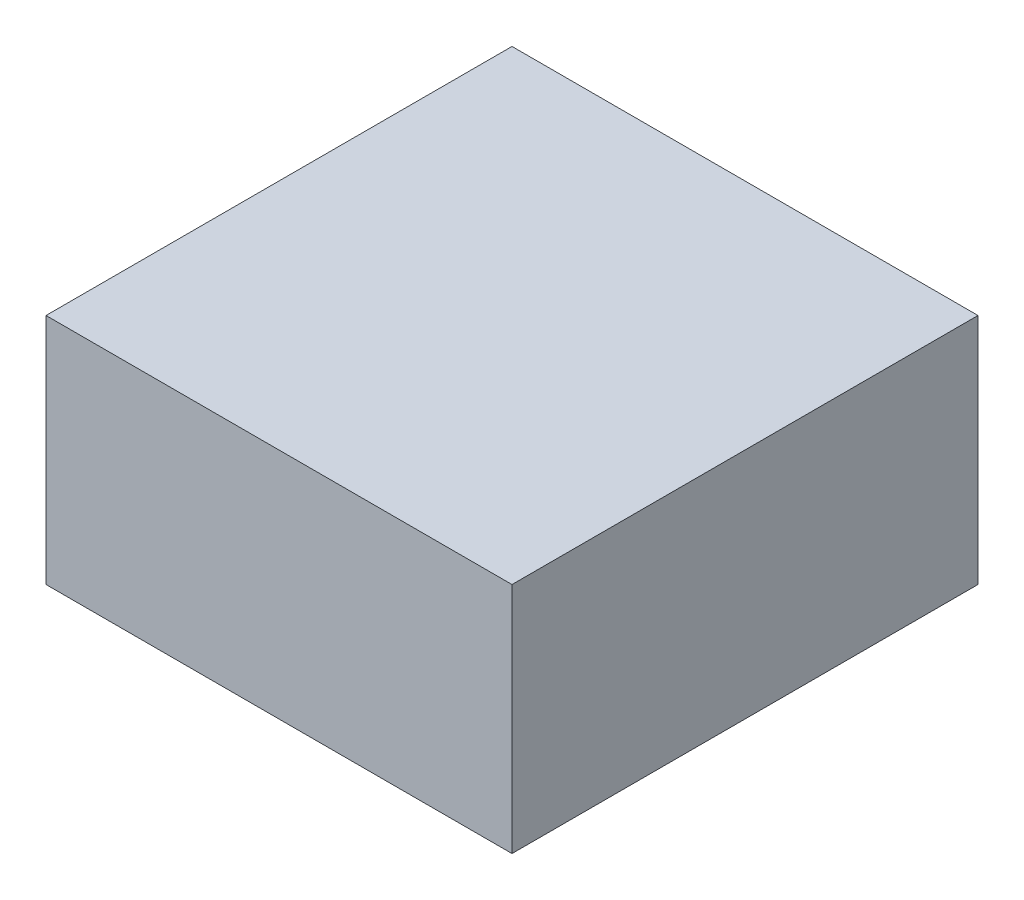
SolidWorks part; units mm, degrees
ref_plane "Front Plane" through (0, 0, 0) normal (0, 0, 1) x (1, 0, 0)
ref_plane "Top Plane" through (0, 0, 0) normal (0, 1, 0) x (1, 0, 0)
ref_plane "Right Plane" through (0, 0, 0) normal (1, 0, 0) x (0, 0, -1)
sketch "Sketch1" plane through (0, 0, 0) normal (0, 1, 0) x (1, 0, 0)
  line L1 (-10.1235, -10.1235) -> (10.1235, -10.1235)
  line L2 (-10.1235, -10.1235) -> (-10.1235, 10.1235)
  line L3 (-10.1235, 10.1235) -> (10.1235, 10.1235)
  line L4 (10.1235, -10.1235) -> (10.1235, 10.1235)
  line L5 (-10.1235, -10.1235) -> (10.1235, 10.1235) construction
  line L6 (-10.1235, 10.1235) -> (10.1235, -10.1235) construction
  point P0 (0, 0)
extrude "Boss-Extrude1" add sketch "Sketch1" along normal blind 10.1235
